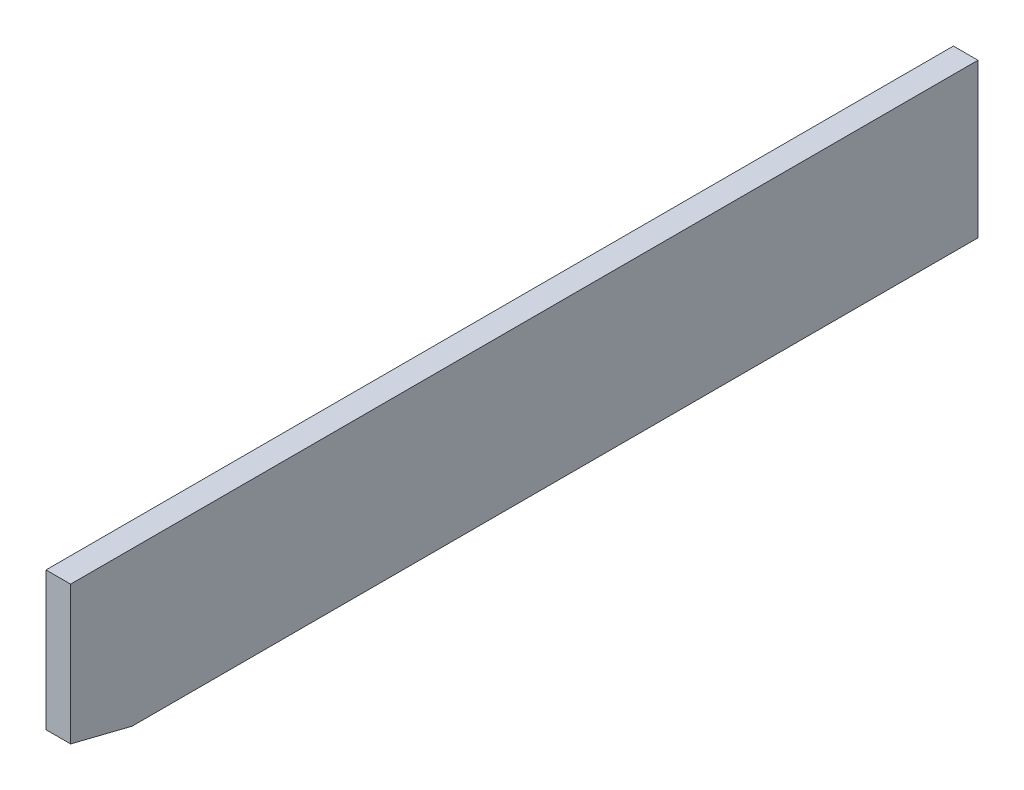
SolidWorks part; units mm, degrees
material "ASTM A36 Steel"
ref_plane "Front Plane" through (0, 0, 0) normal (0, 0, 1) x (1, 0, 0)
ref_plane "Top Plane" through (0, 0, 0) normal (0, 1, 0) x (1, 0, 0)
ref_plane "Right Plane" through (0, 0, 0) normal (1, 0, 0) x (0, 0, -1)
sketch "Sketch1" plane through (0, 0, 0) normal (1, 0, 0) x (0, 0, -1)
  line L0 (-147.5, -20) -> (-127.5, -25)
  line L1 (-127.5, -25) -> (147.5, -25)
  line L2 (-147.5, -20) -> (-147.5, 25)
  line L3 (-147.5, 25) -> (147.5, 25)
  line L4 (147.5, -25) -> (147.5, 25)
  line L5 (-135.5808, -22.9798) -> (147.5, 25) construction
  line L6 (-147.5, 25) -> (147.5, -25) construction
  point P0 (0, 0)
  dimension "D1" = 295
  dimension "D2" = 50
extrude "Boss-Extrude1" add sketch "Sketch1" along normal blind 8
